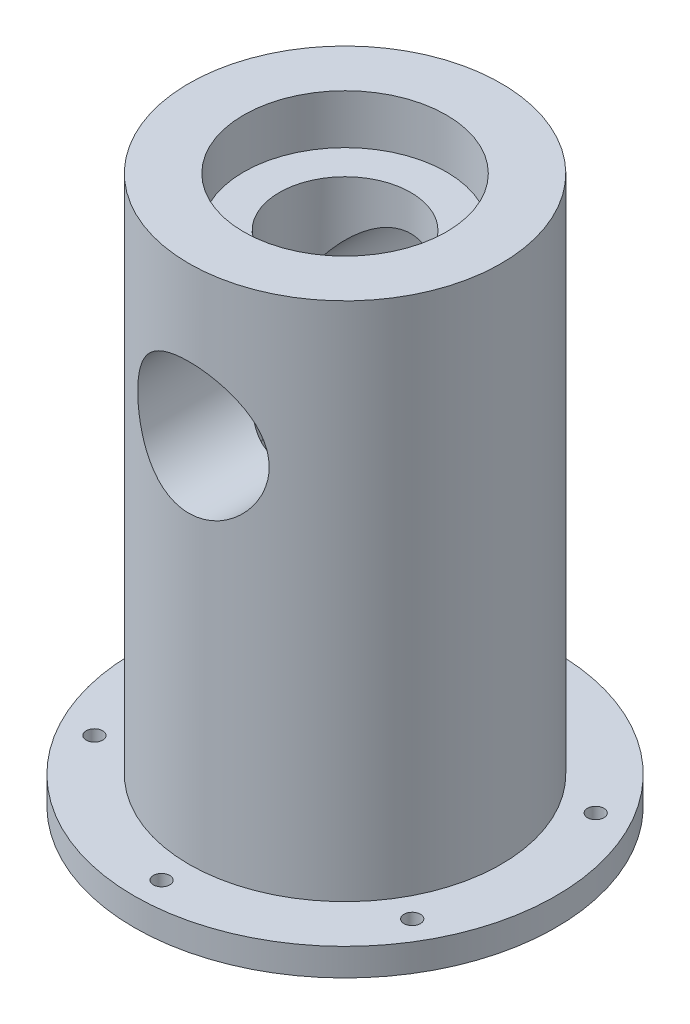
SolidWorks part; units mm, degrees
ref_plane "Plan de face" through (0, 0, 0) normal (0, 0, 1) x (1, 0, 0)
ref_plane "Plan de dessus" through (0, 0, 0) normal (0, 1, 0) x (1, 0, 0)
ref_plane "Plan de droite" through (0, 0, 0) normal (1, 0, 0) x (0, 0, -1)
sketch "Esquisse1" plane through (0, 0, 0) normal (0, 1, 0) x (1, 0, 0)
  circle A0 centre (0, 0) radius 38.5
extrude "Boss.-Extru.1" add sketch "Esquisse1" along normal blind 100
sketch "Esquisse2" plane through (0, 100, 0) normal (0, 1, 0) x (1, 0, 0)
  circle A0 centre (0, 0) radius 38.5
  circle A1 centre (0, 0) radius 28.5
extrude "Enlèv. mat.-Extru.1" cut sketch "Esquisse2" against normal blind 95
sketch "Esquisse3" plane through (0, 100, 0) normal (0, 1, 0) x (1, 0, 0)
  circle A0 centre (0, 0) radius 28.5
sketch "Esquisse4" plane through (0, 0, 0) normal (0, -1, 0) x (-1, 0, 0)
  circle A0 centre (0, 0) radius 22.5
extrude "Enlèv. mat.-Extru.2" cut sketch "Esquisse4" against normal blind 45
sketch "Esquisse5" plane through (0, 45, 0) normal (0, -1, 0) x (-1, 0, 0)
  circle A0 centre (0, 0) radius 18.5
extrude "Enlèv. mat.-Extru.3" cut sketch "Esquisse5" against normal blind 9
sketch "Esquisse6" plane through (0, 54, 0) normal (0, -1, 0) x (-1, 0, 0)
  circle A0 centre (0, 0) radius 12
extrude "Enlèv. mat.-Extru.4" cut sketch "Esquisse6" against normal through all
hole_wizard "Dégagement M222" positions "Esquisse3D2" profile "Esquisse10" hole size "M22" standard "ISO" end condition through all
sketch3d "Esquisse3D2"
  point P0 (0, 72.5, 28.5)
sketch "Esquisse10" plane through (0, 72.5, 28.5) normal (1, 0, 0) x (0, -1, 0)
  line L0 (0, 0) -> (0, 67)
  line L1 (0, 67) -> (12, 67)
  line L2 (12, 67) -> (12, 0)
  line L5 (12, 0) -> (0, 0)
  line L11 (0, -6.35) -> (0, 107.95) construction
  dimension "Diamètre du perçage jusqu'au prochain" = 24
  dimension "Profondeur du perçage jusqu'au prochain" = 67
sketch "Esquisse14" plane through (0, 54, 0) normal (0, -1, 0) x (-1, 0, 0)
  circle A2 centre (0, -33.5) radius 1.5
  circle A3 centre (-29.0119, -16.75) radius 1.5
  circle A4 centre (-29.0119, 16.75) radius 1.5
  circle A5 centre (0, 33.5) radius 1.5
  circle A6 centre (29.0119, 16.75) radius 1.5
  circle A7 centre (29.0119, -16.75) radius 1.5
extrude "Enlèv. mat.-Extru.8" cut sketch "Esquisse14" along normal through all
sketch "Esquisse16" plane through (0, 100, 0) normal (0, 1, 0) x (1, 0, 0)
  circle A0 centre (0, 0) radius 18.5
extrude "Enlèv. mat.-Extru.9" cut sketch "Esquisse16" against normal blind 9
